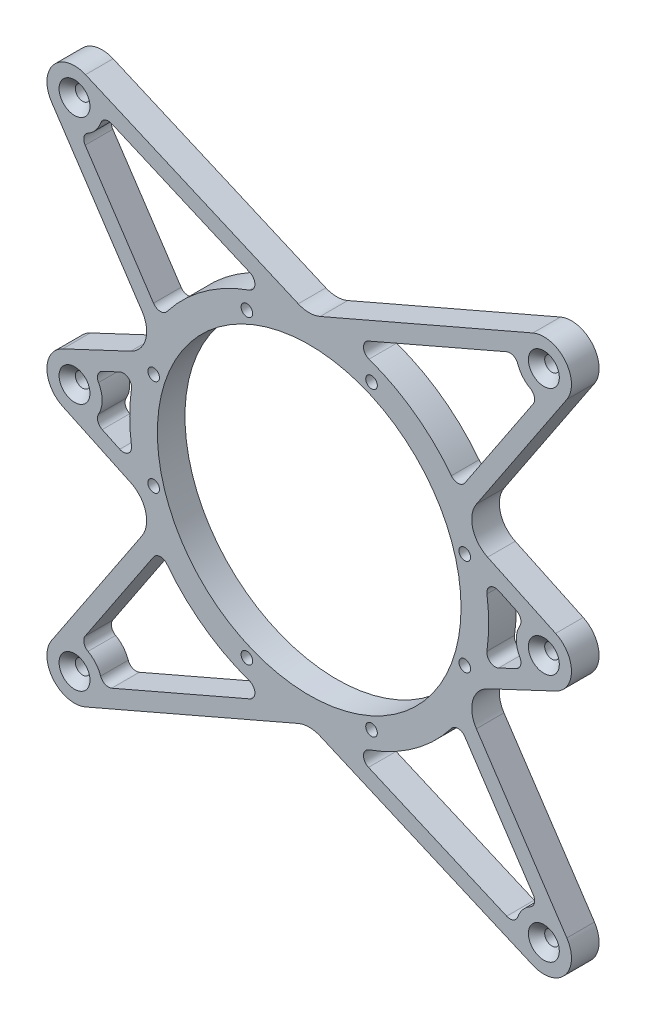
SolidWorks part; units mm, degrees
material "Thornel Mat VMA"
ref_plane "前视基准面" through (0, 0, 0) normal (0, 0, 1) x (1, 0, 0)
ref_plane "上视基准面" through (0, 0, 0) normal (0, 1, 0) x (1, 0, 0)
ref_plane "右视基准面" through (0, 0, 0) normal (1, 0, 0) x (0, 0, -1)
other "Configuration Table"
sketch "草图1" plane through (0, 0, 0) normal (0, 0, 1) x (1, 0, 0)
  line L0 (0, 90) -> (0, -90) construction
  line L1 (-85, 90) -> (-85, -90) construction
  line L2 (85, 90) -> (85, -90) construction
  line L3 (-85, 90) -> (85, -90) construction
  line L4 (-89.3621, 85.8803) -> (80.6379, -94.1197)
  line L5 (-80.6379, 94.1197) -> (89.3621, -85.8803)
  line L6 (85, 90) -> (-85, -90) construction
  line L7 (80.6379, 94.1197) -> (-89.3621, -85.8803)
  line L8 (89.3621, 85.8803) -> (-80.6379, -94.1197)
  line L9 (-85, 0) -> (85, 0) construction
  line L10 (-85, -6) -> (85, -6)
  line L11 (-85, 6) -> (85, 6)
  line L12 (22.5783, 54.5089) -> (0, 0) construction
  line L14 (56.3449, -17.5) -> (-56.3449, -17.5) construction
  line L15 (56.3449, -17.5) -> (56.3449, 17.5) construction
  line L16 (56.3449, 17.5) -> (-56.3449, 17.5) construction
  line L17 (-56.3449, -17.5) -> (-56.3449, 17.5) construction
  line L18 (56.3449, -17.5) -> (-56.3449, 17.5) construction
  line L19 (56.3449, 17.5) -> (-56.3449, -17.5) construction
  line L20 (22.5783, -54.5089) -> (-22.5783, -54.5089) construction
  line L21 (22.5783, -54.5089) -> (22.5783, 54.5089) construction
  line L22 (22.5783, 54.5089) -> (-22.5783, 54.5089) construction
  line L23 (-22.5783, -54.5089) -> (-22.5783, 54.5089) construction
  line L24 (22.5783, -54.5089) -> (-22.5783, 54.5089) construction
  line L25 (22.5783, 54.5089) -> (-22.5783, -54.5089) construction
  circle A0 centre (-85, 90) radius 2.6
  circle A1 centre (0, 90) radius 2.6 construction
  circle A2 centre (85, 90) radius 2.6
  circle A3 centre (85, -90) radius 2.6
  circle A4 centre (0, -90) radius 2.6 construction
  circle A5 centre (-85, -90) radius 2.6
  circle A6 centre (-85, 0) radius 2.6
  circle A7 centre (0, 0) radius 2.6 construction
  circle A8 centre (85, 0) radius 2.6
  circle A9 centre (0, 0) radius 55
  circle A10 centre (-85, 90) radius 6
  circle A11 centre (-85, 0) radius 6
  circle A12 centre (-85, -90) radius 6
  circle A13 centre (85, 90) radius 6
  circle A14 centre (85, 0) radius 6
  circle A15 centre (85, -90) radius 6
  circle A16 centre (0, 0) radius 59 construction
  circle A18 centre (56.3449, 17.5) radius 2.1
  circle A19 centre (56.3449, -17.5) radius 2.1
  circle A22 centre (-56.3449, -17.5) radius 2.1
  circle A23 centre (-56.3449, 17.5) radius 2.1
  circle A29 centre (0, 0) radius 65
  circle A30 centre (-22.5783, 54.5089) radius 2.1
  circle A31 centre (22.5783, 54.5089) radius 2.1
  circle A32 centre (-22.5783, -54.5089) radius 2.1
  circle A33 centre (22.5783, -54.5089) radius 2.1
  point P4 (0, 0)
  point P56 (0, 0)
  dimension "D3" = 5.2
  dimension "D5" = 110
  dimension "D6" = 12
  dimension "D7" = 118
  dimension "D8" = 4.2
  dimension "D10" = 130
  dimension "D1" = 85
  dimension "D4" = 180
  dimension "D11" = 6
  dimension "D13" = 6
  dimension "D15" = 6
  dimension "D17" = 22.5
  dimension "D9" = 35
  dimension "D2" = 85
  dimension "D12" = 6
  dimension "D14" = 6
  dimension "D16" = 6
extrude "凸台-拉伸1" add sketch "草图1" along normal blind 10
sketch "草图2" plane through (0, 0, 10) normal (0, 0, 1) x (1, 0, 0)
  line L0 (0, 75) -> (0, -75) construction
  line L1 (-81.0276, 99.1771) -> (-3.9724, 65.8229)
  line L2 (0, 0) -> (50000, 0) construction
  line L3 (-85, 0) -> (0, 0) construction
  line L4 (0, 0) -> (-85, 90) construction
  line L5 (-59.6916, 25.7277) -> (0, 0) construction
  line L6 (-93.3242, 84.4585) -> (-60.5507, 35.2273)
  line L7 (-89.2561, 9.0491) -> (-64.6188, 20.6368)
  line L8 (3.9724, 65.8229) -> (81.0276, 99.1771)
  line L9 (-68.8749, 29.6858) -> (-59.6916, 25.7277) construction
  line L10 (89.2561, 9.0491) -> (64.6188, 20.6368)
  line L11 (93.3242, 84.4585) -> (60.5507, 35.2273)
  line L12 (-89.2561, -9.0491) -> (-64.6188, -20.6368)
  line L13 (-93.3242, -84.4585) -> (-60.5507, -35.2273)
  line L14 (93.3242, -84.4585) -> (60.5507, -35.2273)
  line L15 (89.2561, -9.0491) -> (64.6188, -20.6368)
  line L16 (3.9724, -65.8229) -> (81.0276, -99.1771)
  line L17 (-81.0276, -99.1771) -> (-3.9724, -65.8229)
  circle A0 centre (-85, 90) radius 10
  circle A1 centre (-85, 0) radius 10
  circle A2 centre (-85, -90) radius 10
  circle A3 centre (85, -90) radius 10
  circle A4 centre (85, 0) radius 10
  circle A5 centre (85, 90) radius 10
  circle A6 centre (85, 0) radius 2.6 construction
  circle A7 centre (85, 90) radius 2.6 construction
  circle A8 centre (85, -90) radius 2.6 construction
  circle A9 centre (-85, -90) radius 2.6 construction
  circle A10 centre (-85, 0) radius 2.6 construction
  circle A11 centre (-85, 90) radius 2.6 construction
  circle A12 centre (85, 0) radius 2.6
  circle A13 centre (85, 90) radius 2.6
  circle A14 centre (85, -90) radius 2.6
  circle A15 centre (-85, -90) radius 2.6
  circle A16 centre (-85, 0) radius 2.6
  circle A17 centre (-85, 90) radius 2.6
  circle A18 centre (0, 75) radius 10
  circle A19 centre (0, -75) radius 10
  arc A24 (-48.8021, 42.9344) -> (-64.7225, 6) centre (0, 0) ccw construction
  arc A28 (40.0779, 51.1738) -> (-40.0779, 51.1738) centre (0, 0) ccw construction
  arc A29 (-48.8021, 42.9344) -> (-64.7225, 6) centre (0, 0) ccw construction
  circle A30 centre (-68.8749, 29.6858) radius 10
  circle A31 centre (68.8749, 29.6858) radius 10
  circle A32 centre (-68.8749, -29.6858) radius 10
  circle A33 centre (68.8749, -29.6858) radius 10
  point P46 (0, 0)
  arc M2 (-40.0779, -51.1738) -> (40.0779, -51.1738) centre (0, 0) ccw
  line M3 (40.0779, -51.1738) -> (80.6379, -94.1197)
  arc M4 (80.6379, -94.1197) -> (89.3621, -85.8803) centre (85, -90) ccw
  line M5 (89.3621, -85.8803) -> (48.8021, -42.9344)
  arc M6 (48.8021, -42.9344) -> (64.7225, -6) centre (0, 0) ccw
  line M7 (64.7225, -6) -> (85, -6)
  arc M8 (85, -6) -> (85, 6) centre (85, 0) ccw
  line M9 (85, 6) -> (64.7225, 6)
  arc M10 (64.7225, 6) -> (48.8021, 42.9344) centre (0, 0) ccw
  line M11 (48.8021, 42.9344) -> (89.3621, 85.8803)
  arc M12 (89.3621, 85.8803) -> (80.6379, 94.1197) centre (85, 90) ccw
  line M13 (80.6379, 94.1197) -> (40.0779, 51.1738)
  arc M14 (40.0779, 51.1738) -> (-40.0779, 51.1738) centre (0, 0) ccw
  line M15 (-40.0779, 51.1738) -> (-80.6379, 94.1197)
  arc M16 (-80.6379, 94.1197) -> (-89.3621, 85.8803) centre (-85, 90) ccw
  line M17 (-89.3621, 85.8803) -> (-48.8021, 42.9344)
  arc M18 (-48.8021, 42.9344) -> (-64.7225, 6) centre (0, 0) ccw
  line M19 (-64.7225, 6) -> (-85, 6)
  arc M20 (-85, 6) -> (-85, -6) centre (-85, 0) ccw
  line M21 (-85, -6) -> (-64.7225, -6)
  arc M22 (-64.7225, -6) -> (-48.8021, -42.9344) centre (0, 0) ccw
  line M23 (-48.8021, -42.9344) -> (-89.3621, -85.8803)
  arc M24 (-89.3621, -85.8803) -> (-80.6379, -94.1197) centre (-85, -90) ccw
  line M25 (-80.6379, -94.1197) -> (-40.0779, -51.1738)
  circle M27 centre (-85, 90) radius 2.6
  circle M35 centre (-85, 0) radius 2.6
  circle M36 centre (85, 90) radius 2.6
  circle M42 centre (-85, -90) radius 2.6
  circle M43 centre (85, -90) radius 2.6
  circle M44 centre (85, 0) radius 2.6
  dimension "D1" = 20
  dimension "D2" = 23.32
extrude "凸台-拉伸3" add sketch "草图2" against normal up to surface (10 mm away) contours A18 L1 A0 M15 M14 | A18 A5 L8 M14 M13 | A30 A0 L6 M18 M17 | A0 M17 M16 M15 | A0 M17 M15 M16 M27 | A30 L7 A1 M19 M18 | L12 A32 A1 M22 M21 | A1 M19 M21 M20 | A1 M21 M19 M20 M35 | A32 L13 A2 M22 M23 | A2 M23 M25 M24 | A2 M25 M23 M24 M42 | A19 A2 L17 M2 M25 | A19 L16 A3 M3 M2 | A3 M5 M4 M3 | A3 M5 M3 M4 M43 | A33 A3 L14 M6 M5 | A33 L15 A4 M7 M6 | A4 M9 M8 M7 | A4 M9 M7 M8 M44 | L10 A31 A4 M10 M9 | A31 L11 A5 M10 M11 | A5 M13 M12 M11 | A5 M13 M11 M12 M36 up to face at (0, 0, 0)
sketch "草图3" plane through (0, 0, 0) normal (0, 0, -1) x (-1, 0, 0)
  line L24 (-6.3559, 60.3166) -> (-83.411, 93.6709)
  line L25 (-88.3297, 87.7834) -> (-55.5562, 38.5522)
  line L26 (-62.0652, 15.2073) -> (-86.7024, 3.6196)
  line L27 (-86.7024, -3.6196) -> (-62.0652, -15.2073)
  line L28 (-55.5562, -38.5522) -> (-88.3297, -87.7834)
  line L29 (-83.411, -93.6709) -> (-6.3559, -60.3166)
  line L30 (6.3559, -60.3166) -> (83.411, -93.6709)
  line L31 (88.3297, -87.7834) -> (55.5562, -38.5522)
  line L32 (62.0652, -15.2073) -> (86.7024, -3.6196)
  line L33 (86.7024, 3.6196) -> (62.0652, 15.2073)
  line L34 (55.5562, 38.5522) -> (88.3297, 87.7834)
  line L35 (83.411, 93.6709) -> (6.3559, 60.3166)
  line L36 (-6.3559, 60.3166) -> (-83.411, 93.6709)
  line L37 (-88.3297, 87.7834) -> (-55.5562, 38.5522)
  line L38 (-62.0652, 15.2073) -> (-86.7024, 3.6196)
  line L39 (-86.7024, -3.6196) -> (-62.0652, -15.2073)
  line L40 (-55.5562, -38.5522) -> (-88.3297, -87.7834)
  line L41 (-83.411, -93.6709) -> (-6.3559, -60.3166)
  line L42 (6.3559, -60.3166) -> (83.411, -93.6709)
  line L43 (88.3297, -87.7834) -> (55.5562, -38.5522)
  line L44 (62.0652, -15.2073) -> (86.7024, -3.6196)
  line L45 (86.7024, 3.6196) -> (62.0652, 15.2073)
  line L46 (55.5562, 38.5522) -> (88.3297, 87.7834)
  line L47 (83.411, 93.6709) -> (6.3559, 60.3166)
  circle A12 centre (-85, 90) radius 10
  circle A13 centre (-85, 0) radius 10
  circle A14 centre (-85, -90) radius 10
  circle A15 centre (85, -90) radius 10
  circle A16 centre (85, 0) radius 10
  circle A17 centre (85, 90) radius 10
  circle A20 centre (0, 0) radius 65
  circle A21 centre (0, 0) radius 65
  arc A24 (-6.3559, 60.3166) -> (6.3559, 60.3166) centre (0, 75) ccw
  arc A25 (-83.411, 93.6709) -> (-88.3297, 87.7834) centre (-85, 90) ccw
  arc A26 (-62.0652, 15.2073) -> (-55.5562, 38.5522) centre (-68.8749, 29.6858) ccw
  arc A27 (-86.7024, 3.6196) -> (-86.7024, -3.6196) centre (-85, 0) ccw
  arc A28 (-55.5562, -38.5522) -> (-62.0652, -15.2073) centre (-68.8749, -29.6858) ccw
  arc A29 (-88.3297, -87.7834) -> (-83.411, -93.6709) centre (-85, -90) ccw
  arc A30 (6.3559, -60.3166) -> (-6.3559, -60.3166) centre (0, -75) ccw
  arc A31 (83.411, -93.6709) -> (88.3297, -87.7834) centre (85, -90) ccw
  arc A32 (62.0652, -15.2073) -> (55.5562, -38.5522) centre (68.8749, -29.6858) ccw
  arc A33 (86.7024, -3.6196) -> (86.7024, 3.6196) centre (85, 0) ccw
  arc A34 (55.5562, 38.5522) -> (62.0652, 15.2073) centre (68.8749, 29.6858) ccw
  arc A35 (88.3297, 87.7834) -> (83.411, 93.6709) centre (85, 90) ccw
  arc A36 (-6.3559, 60.3166) -> (6.3559, 60.3166) centre (0, 75) ccw
  arc A37 (-83.411, 93.6709) -> (-88.3297, 87.7834) centre (-85, 90) ccw
  arc A38 (-62.0652, 15.2073) -> (-55.5562, 38.5522) centre (-68.8749, 29.6858) ccw
  arc A39 (-86.7024, 3.6196) -> (-86.7024, -3.6196) centre (-85, 0) ccw
  arc A40 (-55.5562, -38.5522) -> (-62.0652, -15.2073) centre (-68.8749, -29.6858) ccw
  arc A41 (-88.3297, -87.7834) -> (-83.411, -93.6709) centre (-85, -90) ccw
  arc A42 (6.3559, -60.3166) -> (-6.3559, -60.3166) centre (0, -75) ccw
  arc A43 (83.411, -93.6709) -> (88.3297, -87.7834) centre (85, -90) ccw
  arc A44 (62.0652, -15.2073) -> (55.5562, -38.5522) centre (68.8749, -29.6858) ccw
  arc A45 (86.7024, -3.6196) -> (86.7024, 3.6196) centre (85, 0) ccw
  arc A46 (55.5562, 38.5522) -> (62.0652, 15.2073) centre (68.8749, 29.6858) ccw
  arc A47 (88.3297, 87.7834) -> (83.411, 93.6709) centre (85, 90) ccw
  dimension "D2" = 20
  dimension "D1" = 6
  dimension "D3" = 10
extrude "切除-拉伸1" cut sketch "草图3" against normal blind 30 contours A38 A21 L36 A12 L37 | A21 L38 A13 L39 | A40 L40 A14 L41 A21 | A44 A21 L42 A15 L43 | A21 L44 A16 L45 | A46 L46 A17 L47 A21
fillet "圆角1" radius 3 24 edges at (-75, 90.0301, 5) (-83.2508, 80.1542, 5) (-54.1526, 35.9512, 5) (-78.4088, 7.5204, 5) (-78.4088, -7.5204, 5) (-63.337, -14.6091, 5) (-63.337, 14.6091, 5) (-83.2508, -80.1542, 5) (-75, -90.0301, 5) (-13.7682, -63.5251, 5) (-54.1526, -35.9512, 5) (13.7682, -63.5251, 5) (75, -90.0301, 5) (83.2508, -80.1542, 5) (54.1526, -35.9512, 5) (78.4088, -7.5204, 5) (78.4088, 7.5204, 5) (63.337, 14.6091, 5) (63.337, -14.6091, 5) (83.2508, 80.1542, 5) (75, 90.0301, 5) (13.7682, 63.5251, 5) (54.1526, 35.9512, 5) (-13.7682, 63.5251, 5)
hole_wizard "M5 开槽半沉头木螺钉的锥形沉头孔1" positions "3D草图1" profile "草图4" countersink size "M5" standard "GB"
sketch3d "3D草图1"
  line L0 (85, 90, 10) -> (85, 90, 0) construction
  line L1 (85, 0, 10) -> (85, 0, 0) construction
  line L2 (-85, -90, 10) -> (-85, -90, 0) construction
  line L3 (-85, -90, 0) -> (-85, -90, 10) construction
  line L4 (-85, 0, 10) -> (-85, 0, 0) construction
  line L5 (85, -90, 10) -> (85, -90, 0) construction
  line L6 (85, -90, 0) -> (85, -90, 10) construction
  line L7 (-85, 90, 10) -> (-85, 90, 0) construction
  point P0 (-85, 90, 10)
  point P2 (85, 90, 10)
  point P6 (85, 0, 10)
  point P10 (-85, -90, 10)
  point P16 (-85, 0, 10)
  point P20 (85, -90, 10)
sketch "草图4" plane through (-85, 90, 10) normal (1, 0, 0) x (0, -1, 0)
  line L0 (0, 0) -> (0, 23.9923)
  line L1 (0, 23.9923) -> (2.65, 22.4)
  line L2 (2.65, 22.4) -> (2.65, 2.95)
  line L3 (2.65, 2.95) -> (5.6, 0)
  line L5 (5.6, 0) -> (0, 0)
  line L6 (-2.65, 2.95) -> (-5.6, 0) construction
  line L10 (0, 23.9923) -> (-2.65, 22.4) construction
  line L11 (0, -6.35) -> (0, 107.95) construction
  dimension "孔直径" = 5.3
  dimension "孔深度" = 22.4
  dimension "近端锥形沉头孔直径" = 11.2
  dimension "近端锥形沉头孔角度" = 90
  dimension "导头角度" = 118
hole_wizard "M5 开槽半沉头木螺钉的锥形沉头孔2" positions "草图5" profile "草图6" countersink size "M5" standard "GB"
sketch "草图5" plane through (0, 0, 10) normal (0, 0, 1) x (1, 0, 0)
  point P0 (-85, -90)
  point P3 (85, -90)
sketch "草图6" plane through (-85, -90, 10) normal (1, 0, 0) x (0, -1, 0)
  line L0 (0, 0) -> (0, 23.9923)
  line L1 (0, 23.9923) -> (2.65, 22.4)
  line L2 (2.65, 22.4) -> (2.65, 2.95)
  line L3 (2.65, 2.95) -> (5.6, 0)
  line L5 (5.6, 0) -> (0, 0)
  line L6 (-2.65, 2.95) -> (-5.6, 0) construction
  line L10 (0, 23.9923) -> (-2.65, 22.4) construction
  line L11 (0, -6.35) -> (0, 107.95) construction
  dimension "孔直径" = 5.3
  dimension "孔深度" = 22.4
  dimension "近端锥形沉头孔直径" = 11.2
  dimension "近端锥形沉头孔角度" = 90
  dimension "导头角度" = 118
